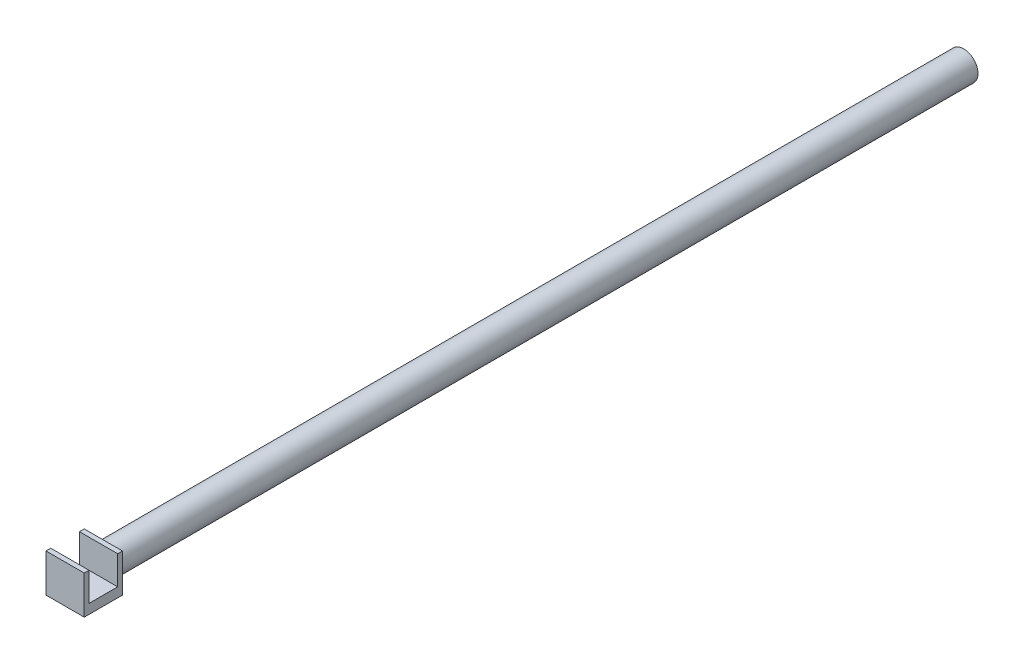
SolidWorks part; units mm, degrees
ref_plane "Front Plane" through (0, 0, 0) normal (0, 0, 1) x (1, 0, 0)
ref_plane "Top Plane" through (0, 0, 0) normal (0, 1, 0) x (1, 0, 0)
ref_plane "Right Plane" through (0, 0, 0) normal (1, 0, 0) x (0, 0, -1)
sketch "Sketch2" plane through (0, 0, 0) normal (1, 0, 0) x (0, 0, -1)
  line L0 (0, -287.9809) -> (0, 14111.0629) construction
  line L1 (-287.9809, 0) -> (14111.0629, 0) construction
  line L2 (7.5, 7.5) -> (10, 7.5)
  line L7 (-7.5, -7.5) -> (7.5, -7.5)
  line L8 (-7.5, -7.5) -> (-7.5, 7.5)
  line L10 (7.5, -7.5) -> (7.5, 7.5)
  line L11 (-7.5, -7.5) -> (7.5, 7.5) construction
  line L12 (-7.5, 7.5) -> (7.5, -7.5) construction
  line L17 (-10, 7.5) -> (-7.5, 7.5)
  line L18 (-10, 7.5) -> (-10, -12.5)
  line L19 (-10, -12.5) -> (10, -12.5)
  line L20 (10, 7.5) -> (10, -12.5)
  point P4 (0, 0)
  point P10 (0, -10.157)
  dimension "D1" = 15
  dimension "D3" = 20
  dimension "D2" = 15
  dimension "D4" = 20
extrude "Boss-Extrude1" add sketch "Sketch2" along normal mid plane 20
sketch "Sketch4" plane through (0, 0, -10) normal (0, 0, -1) x (-1, 0, 0)
  line L0 (0, -1000) -> (0, 49000) construction
  line L4 (-10, 7.5) -> (10, 7.5) construction
  circle A0 centre (0, -2.5) radius 7.5
  dimension "D1" = 10
  dimension "D2" = 15
extrude "Boss-Extrude2" add sketch "Sketch4" along normal blind 450
